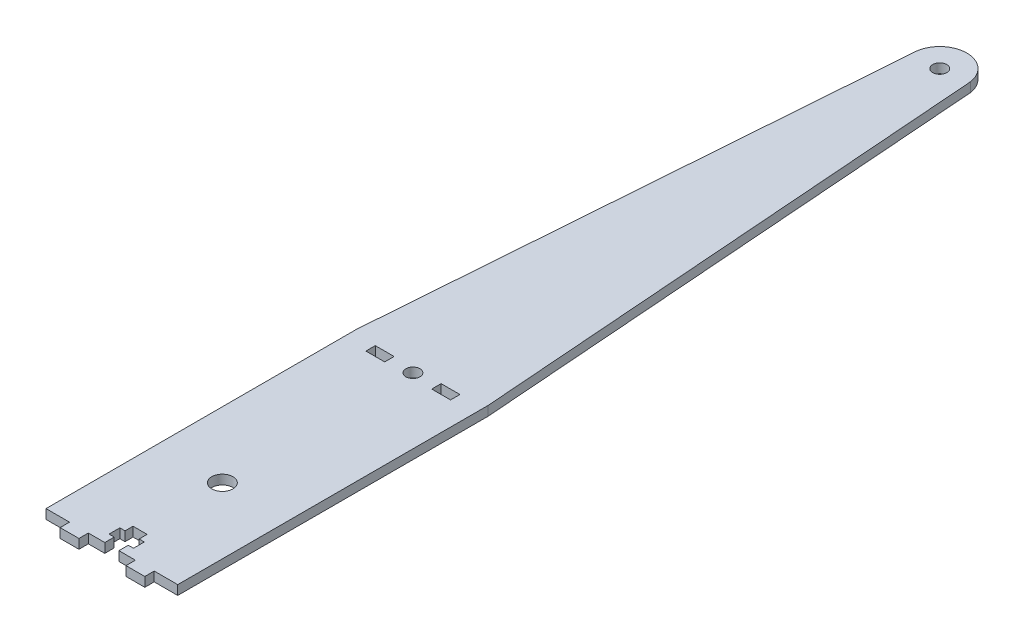
SolidWorks part; units mm, degrees
ref_plane "Front Plane" through (0, 0, 0) normal (0, 0, 1) x (1, 0, 0)
ref_plane "Top Plane" through (0, 0, 0) normal (0, 1, 0) x (1, 0, 0)
ref_plane "Right Plane" through (0, 0, 0) normal (1, 0, 0) x (0, 0, -1)
sketch "Sketch1" plane through (0, 0, 0) normal (0, 1, 0) x (1, 0, 0)
  line L0 (0, 33) -> (28, 33) construction
  line L1 (0, 0) -> (5, 0)
  line L2 (0, 0) -> (0, 66)
  line L3 (0, 66) -> (28, 66)
  line L4 (28, 0) -> (28, 66)
  line L5 (14, 66) -> (14, 0) construction
  line L6 (14, 57.25) -> (18.75, 57.25) construction
  line L13 (5, 0) -> (5, -2)
  line L19 (12.5, 6) -> (15.5, 6)
  line L20 (12.5, 6) -> (12.5, 4.3)
  line L33 (15.5, 6) -> (15.5, 4.3)
  line L34 (12.5, 6) -> (15.5, 0) construction
  line L35 (12.5, 0) -> (15.5, 6) construction
  line L36 (15.5, 2) -> (16.6, 2)
  line L38 (15.5, 4.3) -> (16.6, 4.3)
  line L39 (16.6, 2) -> (16.6, 4.3)
  line L41 (19, 0) -> (19, -2)
  line L42 (19, -2) -> (23, -2)
  line L43 (23, 0) -> (23, -2)
  line L44 (9, -2) -> (5, -2)
  line L45 (9, 0) -> (9, -2)
  line L46 (12.5, 2) -> (11.4, 2)
  line L47 (11.4, 2) -> (11.4, 4.3)
  line L48 (12.5, 4.3) -> (11.4, 4.3)
  line L49 (9, 0) -> (12.5, 0)
  line L50 (23, 0) -> (28, 0)
  line L51 (12.5, 2) -> (12.5, 0)
  line L52 (15.5, 2) -> (15.5, 0)
  line L53 (15.5, 0) -> (19, 0)
  line L54 (14, 64) -> (21, 64) construction
  line L55 (5, 65) -> (9, 65)
  line L56 (23, 63) -> (19, 63)
  line L57 (23, 63) -> (23, 65)
  line L58 (23, 65) -> (19, 65)
  line L59 (19, 63) -> (19, 65)
  line L60 (23, 63) -> (19, 65) construction
  line L61 (23, 65) -> (19, 63) construction
  line L62 (9, 63) -> (9, 65)
  line L63 (5, 63) -> (9, 63)
  line L64 (5, 63) -> (5, 65)
  circle A6 centre (14, 64) radius 1.5
  circle A7 centre (14, 23.49) radius 2.25
  point P9 (14, 33)
  point P23 (14, 3)
  point P36 (19, -1)
  dimension "D8" = 5
  dimension "D18" = 3
  dimension "D3" = 4.5
  dimension "D4" = 9.51
  dimension "D1" = 28
  dimension "D2" = 66
  dimension "D6" = 4.75
  dimension "D9" = 4
  dimension "D10" = 2
  dimension "D11" = 3
  dimension "D12" = 6
  dimension "D13" = 1.1
  dimension "D14" = 2.3
  dimension "D15" = 2
  dimension "D16" = 4
  dimension "D17" = 2
  dimension "D19" = 5
  dimension "D20" = 1
extrude "Boss-Extrude1" add sketch "Sketch1" along normal blind 2
sketch "Sketch2" plane through (0, 2, 0) normal (0, 1, 0) x (1, 0, 0)
  line L1 (28, 66) -> (0, 66)
  line L2 (14, 66) -> (14, 186) construction
  line L3 (9, 186) -> (0, 66)
  line L4 (28, 66) -> (19, 186)
  arc A0 (19, 186) -> (9, 186) centre (14, 186) ccw
  dimension "D1" = 10
  dimension "D2" = 120
extrude "Boss-Extrude2" add sketch "Sketch2" against normal blind 2
sketch "Sketch3" plane through (0, 2, 0) normal (0, 1, 0) x (1, 0, 0)
  line L0 (0, 66) -> (28, 66) construction
  line L1 (14, 66) -> (14, 176) construction
  line L2 (15.5, 176) -> (19.75, 176) construction
  line L3 (9, 186) -> (0, 66) construction
  line L4 (28, 66) -> (19, 186) construction
  line L5 (19.75, 176) -> (22.0064, 176)
  line L6 (5.1308, 176) -> (8.25, 176)
  line L7 (5.1308, 176) -> (5.1308, 202.1062)
  line L8 (5.1308, 202.1062) -> (22.0064, 202.1062)
  line L9 (22.0064, 176) -> (22.0064, 202.1062)
  circle A0 centre (14, 176) radius 1.5
  arc A1 (8.25, 176) -> (19.75, 176) centre (14, 176) cw
  dimension "D1" = 3
  dimension "D2" = 110
extrude "Cut-Extrude1" cut sketch "Sketch3" against normal blind 2
